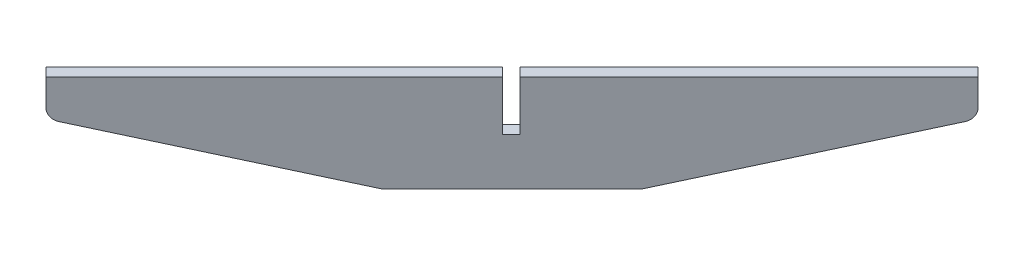
SolidWorks part; units mm, degrees
ref_plane "Front Plane" through (0, 0, 0) normal (0, 0, 1) x (1, 0, 0)
ref_plane "Top Plane" through (0, 0, 0) normal (0, 1, 0) x (1, 0, 0)
ref_plane "Right Plane" through (0, 0, 0) normal (1, 0, 0) x (0, 0, -1)
sketch "Sketch1" plane through (0, 0, 0) normal (0, 1, 0) x (1, 0, 0)
  line L0 (-195, -158.5534) -> (-158.5534, -195) construction
  line L1 (-195, 195) -> (195, 195) construction
  line L2 (-195, 195) -> (-195, -195) construction
  line L3 (-195, -195) -> (195, -195) construction
  line L4 (195, 195) -> (195, -195) construction
  line L5 (-195, 195) -> (195, -195) construction
  line L6 (-195, -195) -> (195, 195) construction
  line L7 (-195, -512.1068) -> (-512.1068, -195) construction
  line L8 (-195, -865.6602) -> (-865.6602, -195) construction
  line L9 (-865.6602, 195) -> (-195, 865.6602) construction
  line L10 (-512.1068, 195) -> (-195, 512.1068) construction
  line L11 (-158.5534, 195) -> (-195, 158.5534) construction
  line L12 (195, 865.6602) -> (865.6602, 195) construction
  line L13 (195, 512.1068) -> (512.1068, 195) construction
  line L14 (195, 158.5534) -> (158.5534, 195) construction
  line L15 (865.6602, -195) -> (195, -865.6602) construction
  line L16 (512.1068, -195) -> (195, -512.1068) construction
  line L17 (158.5534, -195) -> (195, -158.5534) construction
  line L18 (-195, -187.9289) -> (-187.9289, -195)
  line L19 (-195, -187.9289) -> (187.9289, 195)
  line L20 (-187.9289, -195) -> (195, 187.9289)
  line L21 (187.9289, 195) -> (195, 187.9289)
  line L22 (-195, 154.3107) -> (-199.2426, 158.5534) construction
  line L23 (-195, 154.3107) -> (-158.5534, 190.7574) construction
  line L24 (-199.2426, 158.5534) -> (-162.796, 195) construction
  line L25 (-158.5534, 190.7574) -> (-162.796, 195) construction
  line L26 (-195, 516.3494) -> (-190.7574, 512.1068) construction
  line L27 (-195, 516.3494) -> (-516.3494, 195) construction
  line L28 (-190.7574, 512.1068) -> (-512.1068, 190.7574) construction
  line L29 (-516.3494, 195) -> (-512.1068, 190.7574) construction
  line L32 (-195, 869.9028) -> (-190.7574, 865.6602) construction
  line L33 (-195, 869.9028) -> (-869.9028, 195) construction
  line L34 (-190.7574, 865.6602) -> (-865.6602, 190.7574) construction
  line L35 (-869.9028, 195) -> (-865.6602, 190.7574) construction
  point P0 (0, 0)
  point P12 (-191.4645, -191.4645)
  point P33 (0, 0)
  point P37 (-197.1213, 156.4321)
  point P40 (-160.6747, 192.8787)
  point P43 (-192.8787, 514.2281)
  point P44 (-192.8787, 867.7815)
  point P45 (-867.7815, 192.8787)
  point P46 (-514.2281, 192.8787)
  dimension "D1" = 390
  dimension "D2" = 250
  dimension "D3" = 250
  dimension "D4" = 250
  dimension "D6" = 250
  dimension "D7" = 250
  dimension "D8" = 10
  dimension "D9" = 6
  dimension "D10" = 6
  dimension "D11" = 6
  dimension "D5" = 4
extrude "Boss-Extrude1" add sketch "Sketch1" along normal mid plane 30
ref_plane "Plane1" through (0, 0, 0) normal (0.7071, 0, 0.7071) x (0.7071, 0, -0.7071)
ref_plane "Plane2" through (0, 0, 0) normal (-0.7071, 0, 0.7071) x (0.7071, 0, 0.7071)
sketch "Sketch2" plane through (0, 0, 0) normal (0.7071, 0, 0.7071) x (0.7071, 0, -0.7071)
  line L0 (0, 149.1941) -> (0, -149.1941) construction
  line L1 (-3.1, 0) -> (3.1, 0)
  line L2 (-3.1, 0) -> (-3.1, 50)
  line L3 (-3.1, 50) -> (3.1, 50)
  line L4 (3.1, 0) -> (3.1, 50)
  line L5 (-3.1, 0) -> (3.1, 50) construction
  line L6 (-3.1, 50) -> (3.1, 0) construction
  line L7 (-253.1, 0) -> (-246.9, 0)
  line L8 (-253.1, 0) -> (-253.1, 50)
  line L9 (-253.1, 50) -> (-246.9, 50)
  line L10 (-246.9, 0) -> (-246.9, 50)
  line L11 (-253.1, 0) -> (-246.9, 50) construction
  line L12 (-253.1, 50) -> (-246.9, 0) construction
  line L13 (-503.1, 0) -> (-496.9, 0)
  line L14 (-503.1, 0) -> (-503.1, 50)
  line L15 (-503.1, 50) -> (-496.9, 50)
  line L16 (-496.9, 0) -> (-496.9, 50)
  line L17 (-503.1, 0) -> (-496.9, 50) construction
  line L18 (-503.1, 50) -> (-496.9, 0) construction
  line L19 (-753.1, 0) -> (-746.9, 0)
  line L20 (-753.1, 0) -> (-753.1, 50)
  line L21 (-753.1, 50) -> (-746.9, 50)
  line L22 (-746.9, 0) -> (-746.9, 50)
  line L23 (-753.1, 0) -> (-746.9, 50) construction
  line L24 (-753.1, 50) -> (-746.9, 0) construction
  line L25 (949.0596, 0) -> (-949.0596, 0) construction
  line L27 (753.1, 50) -> (746.9, 0) construction
  line L28 (753.1, 0) -> (746.9, 50) construction
  line L29 (503.1, 50) -> (496.9, 0) construction
  line L30 (503.1, 0) -> (496.9, 50) construction
  line L31 (253.1, 50) -> (246.9, 0) construction
  line L32 (253.1, 0) -> (246.9, 50) construction
  line L33 (746.9, 0) -> (746.9, 50)
  line L34 (753.1, 50) -> (746.9, 50)
  line L35 (753.1, 0) -> (753.1, 50)
  line L36 (753.1, 0) -> (746.9, 0)
  line L37 (496.9, 0) -> (496.9, 50)
  line L38 (503.1, 50) -> (496.9, 50)
  line L39 (503.1, 0) -> (503.1, 50)
  line L40 (503.1, 0) -> (496.9, 0)
  line L41 (246.9, 0) -> (246.9, 50)
  line L42 (253.1, 50) -> (246.9, 50)
  line L43 (253.1, 0) -> (253.1, 50)
  line L44 (253.1, 0) -> (246.9, 0)
  point P0 (0, 25)
  point P5 (-250, 25)
  point P10 (-500, 25)
  point P15 (-750, 25)
  point P28 (-250, 0)
  point P30 (-500, 0)
  point P32 (-750, 0)
  point P46 (750, 25)
  point P47 (500, 25)
  point P48 (250, 25)
  dimension "D1" = 6.2
  dimension "D2" = 50
extrude "Cut-Extrude1" [suppressed] cut sketch "Sketch2" against normal through all both and the other way through all
sketch "Sketch3" plane through (0, 0, 0) normal (0.7071, 0, 0.7071) x (0.7071, 0, -0.7071)
  line L0 (270.7716, -15) -> (75, -65)
  line L1 (75, -65) -> (-75, -65)
  line L2 (-75, -65) -> (-270.7716, -15)
  line L3 (-270.7716, -15) -> (270.7716, -15)
  line L4 (0, 149.1941) -> (0, -149.1941) construction
  line L5 (270.7716, -15) -> (-270.7716, -15) construction
  point P2 (0, -15)
  point P9 (0, -65)
  dimension "D1" = 50
  dimension "D2" = 150
extrude "Boss-Extrude2" add sketch "Sketch3" along normal mid plane 10
sketch "Sketch4" plane through (0, 0, 0) normal (0.7071, 0, 0.7071) x (0.7071, 0, -0.7071)
  line L1 (-5.5309, -26) -> (4.6691, -26)
  line L2 (-5.5309, -26) -> (-5.5309, 56)
  line L3 (-5.5309, 56) -> (4.6691, 56)
  line L4 (4.6691, -26) -> (4.6691, 56)
  line L5 (-5.5309, -26) -> (4.6691, 56) construction
  line L6 (-5.5309, 56) -> (4.6691, -26) construction
  line L10 (-270.7716, 15) -> (270.7716, 15) construction
  point P0 (-0.4309, 15)
  point P12 (-0.4309, 15)
  dimension "D1" = 10.2
  dimension "D2" = 82
extrude "Cut-Extrude2" cut sketch "Sketch4" against normal through all both and the other way through all
sketch "Sketch5" [suppressed] plane through (0, 0, 0) normal (0.7071, 0, 0.7071) x (0.7071, 0, -0.7071)
  line L0 (0, 149.1941) -> (0, -149.1941) construction
  line L1 (306.127, 15) -> (-306.127, 15) construction
  circle A0 centre (125, -20) radius 4
  circle A1 centre (125, -50) radius 4
  circle A2 centre (40, -35) radius 10
  circle A3 centre (-40, -35) radius 10
  circle A4 centre (-125, -50) radius 4
  circle A5 centre (-125, -20) radius 4
  circle A6 centre (-375, 0) radius 4
  circle A7 centre (-625, 0) radius 4
  circle A8 centre (375, 0) radius 4
  circle A9 centre (625, 0) radius 4
  dimension "D1" = 20
  dimension "D2" = 8
  dimension "D3" = 125
  dimension "D4" = 35
  dimension "D5" = 30
  dimension "D6" = 50
  dimension "D7" = 40
  dimension "D8" = 250
  dimension "D9" = 250
extrude "Cut-Extrude3" [suppressed] cut sketch "Sketch5" against normal through all both and the other way through all
ref_plane "Plane3" through (-3.5355, 0, -3.5355) normal (-0.7071, 0, -0.7071) x (-0.7071, 0, 0.7071)
sketch "Sketch6" plane through (-3.5355, 0, -3.5355) normal (-0.7071, 0, -0.7071) x (-0.7071, 0, 0.7071)
  line L0 (-114.1421, 50) -> (-154.9251, 50) construction
  line L1 (-114.1421, 40) -> (-154.9251, 40)
  line L2 (-114.1421, 50) -> (-114.1421, 40)
  line L3 (-154.9251, 50) -> (-154.9251, 40)
  dimension "D2" = 10
extrude "Cut-Extrude4" [suppressed] cut sketch "Sketch6" against normal through all both and the other way through all
pattern_linear "LPattern1" [suppressed] count 5 spacing 250
ref_plane "Plane4" through (0, 0, 0) normal (-0.7071, 0, 0.7071) x (0.7071, 0, 0.7071)
mirror "Mirror1" [suppressed] about plane through (0, 0, 0) normal (-0.7071, 0, 0.7071)
ref_plane "Plane5" through (0, 0, 0) normal (0.7071, 0, 0.7071) x (0.7071, 0, -0.7071)
fillet "Fillet1" radius 10 2 edges at (191.4645, -15, -191.4645) (-191.4645, -15, 191.4645)
